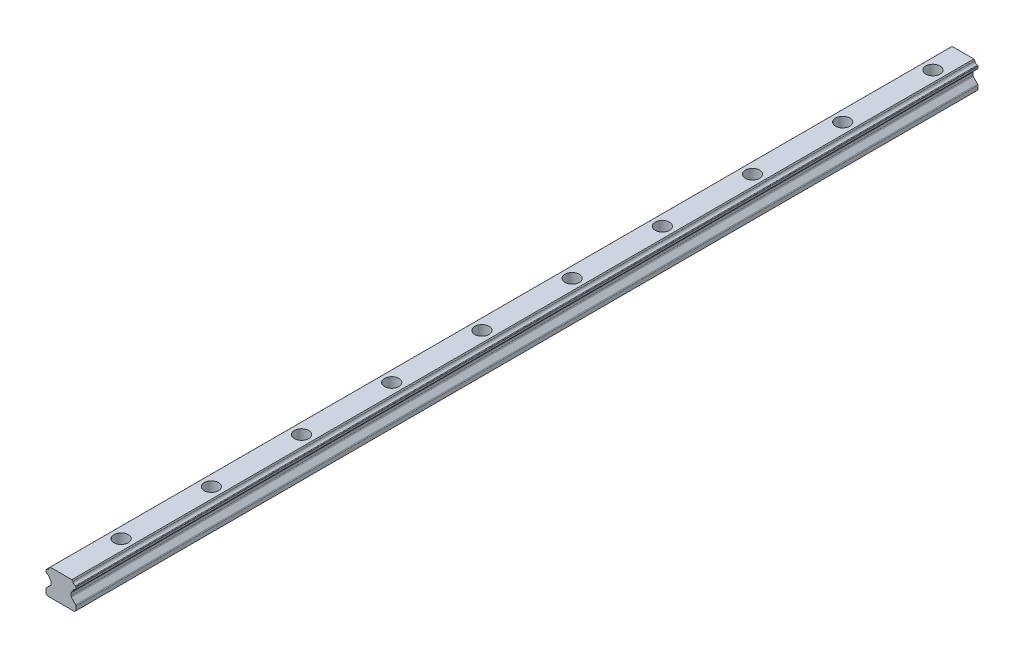
SolidWorks part; units mm, degrees
ref_plane "Front Plane" through (0, 0, 0) normal (0, 0, 1) x (1, 0, 0)
ref_plane "Top Plane" through (0, 0, 0) normal (0, 1, 0) x (1, 0, 0)
ref_plane "Right Plane" through (0, 0, 0) normal (1, 0, 0) x (0, 0, -1)
sketch "Model" plane through (0, 0, 0) normal (0, 0, 1) x (1, 0, 0)
  line L0 (-9, 0) -> (-10, 1)
  line L1 (9.7071, 4.3636) -> (6.8929, 7.1778)
  line L2 (-9.6906, 12.9499) -> (-9.8536, 13.1128)
  line L3 (7.6325, 17.0982) -> (7.2307, 17.5)
  line L4 (-6.8929, 10.1522) -> (-7.6302, 10.8894)
  line L5 (9.8536, 14.8772) -> (9.6785, 15.0522)
  line L6 (-9, 0) -> (9, 0)
  line L7 (-7.2307, 17.5) -> (7.2307, 17.5)
  line L8 (-9.8536, 14.8772) -> (-9.6785, 15.0522)
  line L9 (6.8929, 10.1522) -> (7.6302, 10.8894)
  line L10 (9, 0) -> (10, 1)
  line L11 (-9.7071, 4.3636) -> (-6.8929, 7.1778)
  line L12 (9.6906, 12.9499) -> (9.8536, 13.1128)
  line L13 (-7.6325, 17.0982) -> (-7.2307, 17.5)
  line L14 (-10, 1) -> (-10, 3.6565)
  line L15 (-10, 13.4664) -> (-10, 14.5236)
  line L16 (-6.6, 7.8849) -> (-6.6, 9.4451)
  line L17 (6.6, 7.8849) -> (6.6, 9.4451)
  line L18 (10, 1) -> (10, 3.6565)
  line L19 (10, 13.4664) -> (10, 14.5236)
  arc A0 (-7.8468, 11.2275) -> (-9.4318, 12.8125) centre (-9.8106, 10.8487) ccw
  arc A1 (-9.422, 15.1892) -> (-7.8482, 16.763) centre (-9.8101, 17.1511) ccw
  arc A2 (-10, 13.4664) -> (-9.8536, 13.1128) centre (-9.5, 13.4664) ccw
  arc A3 (-9.8536, 14.8772) -> (-10, 14.5236) centre (-9.5, 14.5236) ccw
  arc A4 (-9.6906, 12.9499) -> (-9.4318, 12.8125) centre (-9.3371, 13.3035) ccw
  arc A5 (-9.422, 15.1892) -> (-9.6785, 15.0522) centre (-9.3249, 14.6987) ccw
  arc A6 (-9.7071, 4.3636) -> (-10, 3.6565) centre (-9, 3.6565) ccw
  arc A7 (-6.8929, 7.1778) -> (-6.6, 7.8849) centre (-7.6, 7.8849) ccw
  arc A8 (-6.6, 9.4451) -> (-6.8929, 10.1522) centre (-7.6, 9.4451) ccw
  arc A9 (-7.6325, 17.0982) -> (-7.8482, 16.763) centre (-7.3547, 16.6825) ccw
  arc A10 (-7.8468, 11.2275) -> (-7.6302, 10.8894) centre (-7.3529, 11.3055) ccw
  arc A11 (7.6302, 10.8894) -> (7.8468, 11.2275) centre (7.3529, 11.3055) ccw
  arc A12 (7.8482, 16.763) -> (7.6325, 17.0982) centre (7.3547, 16.6825) ccw
  arc A13 (6.6, 7.8849) -> (6.8929, 7.1778) centre (7.6, 7.8849) ccw
  arc A14 (6.8929, 10.1522) -> (6.6, 9.4451) centre (7.6, 9.4451) ccw
  arc A15 (10, 3.6565) -> (9.7071, 4.3636) centre (9, 3.6565) ccw
  arc A16 (9.6785, 15.0522) -> (9.422, 15.1892) centre (9.3249, 14.6987) ccw
  arc A17 (9.4318, 12.8125) -> (9.6906, 12.9499) centre (9.3371, 13.3035) ccw
  arc A18 (9.8536, 13.1128) -> (10, 13.4664) centre (9.5, 13.4664) ccw
  arc A19 (10, 14.5236) -> (9.8536, 14.8772) centre (9.5, 14.5236) ccw
  arc A20 (7.8482, 16.763) -> (9.422, 15.1892) centre (9.8101, 17.1511) ccw
  arc A21 (9.4318, 12.8125) -> (7.8468, 11.2275) centre (9.8106, 10.8487) ccw
extrude "Boss-Extrude1" add sketch "Model" along normal blind 600
hole_wizard "CBORE for M5 Hex Head Bolt1" positions "Sketch4" profile "Sketch5" counterbore size "M5" standard "ANSI Metric" end condition through all
sketch "Sketch4" plane through (0, 17.5, 0) normal (0, 1, 0) x (1, 0, 0)
  line L0 (7.2307, 0) -> (-7.2307, 0) construction
  point P0 (0, -20)
  point P8 (0, 0)
  point P14 (0, -80)
  point P15 (0, -140)
  point P16 (0, -200)
  point P17 (0, -260)
  point P18 (0, -320)
  point P19 (0, -380)
  point P20 (0, -440)
  point P21 (0, -500)
  point P22 (0, -560)
  point P23 (0, -620)
  point P24 (0, -680)
  point P25 (0, -740)
  point P26 (0, -800)
  point P27 (0, -860)
  point P28 (0, -920)
  point P29 (0, -980)
  dimension "D1" = 20
  dimension "D3" = 60
  dimension "D2" = 17
sketch "Sketch5" plane through (0, 17.5, 20) normal (1, 0, 0) x (0, 0, 1)
  line L0 (0, 0) -> (0, 17.5)
  line L1 (0, 17.5) -> (3, 17.5)
  line L3 (3, 17.5) -> (3, 8.5)
  line L4 (3, 8.5) -> (4.75, 8.5)
  line L5 (4.75, 8.5) -> (4.75, 0)
  line L7 (4.75, 0) -> (0, 0)
  line L11 (0, -6.35) -> (0, 107.95) construction
  dimension "Thru Hole Dia." = 6
  dimension "Thru Hole Depth" = 17.5
  dimension "C'Bore Dia." = 9.5
  dimension "C'Bore Depth" = 8.5
